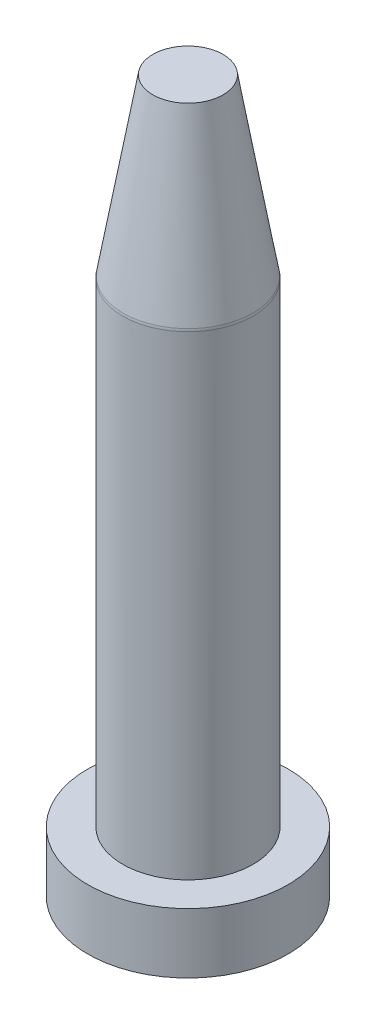
SolidWorks part; units mm, degrees
ref_plane "前视" through (0, 0, 0) normal (0, 0, 1) x (1, 0, 0)
ref_plane "上视" through (0, 0, 0) normal (0, 1, 0) x (1, 0, 0)
ref_plane "右视" through (0, 0, 0) normal (1, 0, 0) x (0, 0, -1)
sketch "草图1" plane through (0, 0, 0) normal (0, 0, 1) x (1, 0, 0)
  line L0 (0, 0) -> (0, 101.922) construction
  line L1 (0, 0) -> (20, 0)
  line L2 (20, 0) -> (20, 12)
  line L3 (20, 12) -> (13, 12)
  line L4 (13, 12) -> (13, 107)
  line L5 (0, 142) -> (7, 142)
  line L6 (7, 142) -> (13, 107)
  line L7 (0, 0) -> (0, 142)
  point P7 (0, 142)
  dimension "D1" = 20
  dimension "D2" = 12
  dimension "D3" = 7
  dimension "D4" = 95
  dimension "D5" = 142
  dimension "D6" = 7
revolve "基体-旋转" add sketch "草图1" angle 360 about L0
fillet "圆角1" radius 3 1 edges at (0, 107, -13)
